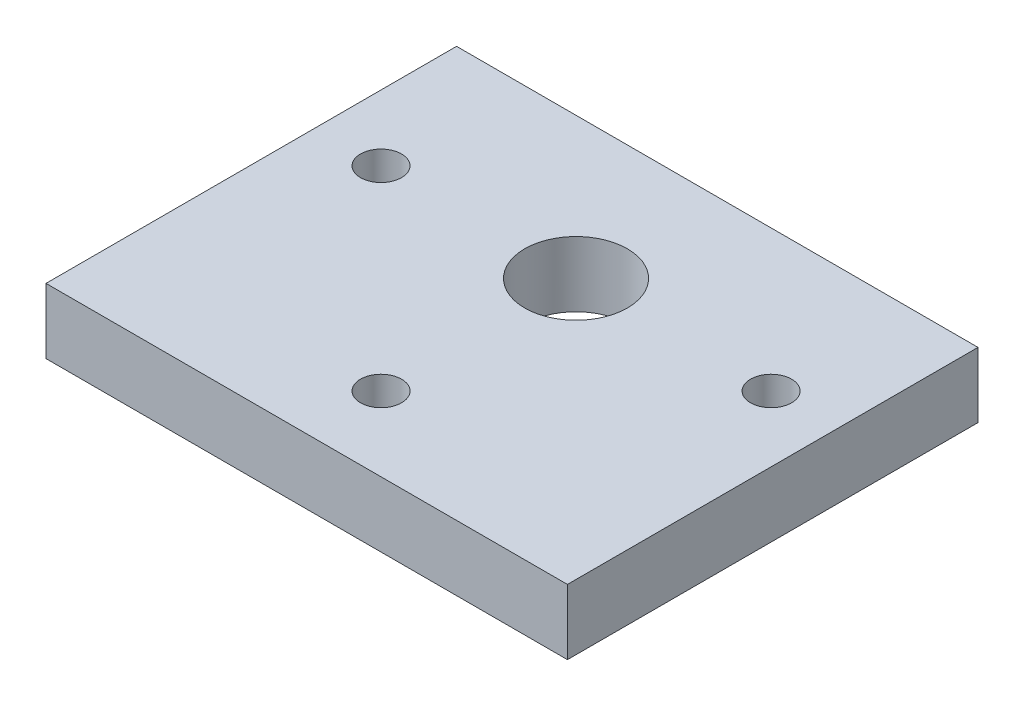
SolidWorks part; units mm, degrees
ref_plane "Alzado" through (0, 0, 0) normal (0, 0, 1) x (1, 0, 0)
ref_plane "Planta" through (0, 0, 0) normal (0, 1, 0) x (1, 0, 0)
ref_plane "Vista lateral" through (0, 0, 0) normal (1, 0, 0) x (0, 0, -1)
sketch "Croquis1" plane through (0, 0, 0) normal (0, 1, 0) x (1, 0, 0)
  line L1 (-25.4, 40) -> (25.4, 40)
  line L2 (-25.4, 40) -> (-25.4, -40)
  line L3 (-25.4, -40) -> (25.4, -40)
  line L4 (25.4, 40) -> (25.4, -40)
  line L5 (-25.4, 40) -> (25.4, -40) construction
  line L6 (-25.4, -40) -> (25.4, 40) construction
  point P0 (0, 0)
  dimension "D1" = 80
  dimension "D2" = 50.8
extrude "Saliente-Extruir1" add sketch "Croquis1" along normal blind 6.35
sketch "Croquis4" plane through (0, 6.35, 0) normal (0, 1, 0) x (1, 0, 0)
  circle A0 centre (-19, 19.4661) radius 2
  circle A1 centre (19, 19.4661) radius 2
  circle A2 centre (0, 0.4661) radius 2
  dimension "D3" = 4
  dimension "D5" = 4
  dimension "D4" = 4
  dimension "D1" = 38
  dimension "D2" = 19
  dimension "D6" = 19
extrude "Cortar-Extruir3" cut sketch "Croquis4" against normal through all
sketch "Croquis5" plane through (0, 6.35, 0) normal (0, 1, 0) x (1, 0, 0)
  line L0 (25.4, -40) -> (25.4, 40) construction
  line L1 (-25.4, -40) -> (25.4, -40)
  line L2 (-25.4, -40) -> (-25.4, -27.3)
  line L3 (-25.4, -27.3) -> (25.4, -27.3)
  line L4 (25.4, -40) -> (25.4, -27.3)
  dimension "D1" = 12.7
extrude "Cortar-Extruir4" cut sketch "Croquis5" against normal through all
sketch "Croquis6" plane through (0, 6.35, 0) normal (0, 1, 0) x (1, 0, 0)
  line L0 (25.4, -27.3) -> (25.4, 40) construction
  line L1 (-25.4, -27.3) -> (25.4, -27.3)
  line L2 (-25.4, -27.3) -> (-25.4, -6.7734)
  line L3 (-25.4, -6.7734) -> (25.4, -6.7734)
  line L4 (25.4, -27.3) -> (25.4, -6.7734)
extrude "Cortar-Extruir5" cut sketch "Croquis6" against normal blind 10
sketch "Croquis7" plane through (0, 0, 0) normal (0, -1, 0) x (1, 0, 0)
  line L0 (25.4, 6.7734) -> (25.4, -40) construction
  line L1 (-25.4, 6.7734) -> (25.4, 6.7734)
  line L2 (-25.4, 6.7734) -> (-25.4, -33.2266)
  line L3 (-25.4, -33.2266) -> (25.4, -33.2266)
  line L4 (25.4, 6.7734) -> (25.4, -33.2266)
  line L6 (-25.4, -33.2266) -> (25.4, -33.2266)
  line L7 (-25.4, -33.2266) -> (-25.4, -40)
  line L8 (-25.4, -40) -> (25.4, -40)
  line L9 (25.4, -33.2266) -> (25.4, -40)
  line M5 (25.4, -40) -> (25.4, 6.7734)
  line M7 (-25.4, 6.7734) -> (-25.4, -40)
  line M8 (-25.4, -40) -> (25.4, -40)
  dimension "D1" = 40
extrude "Cortar-Extruir6" cut sketch "Croquis7" against normal blind 10 contours L3 M7 M8 M5
sketch "Croquis9" plane through (0, 0, 0) normal (0, -1, 0) x (1, 0, 0)
  line L0 (-19, -19.4661) -> (19, -19.4661) construction
  circle A0 centre (0, -19.4661) radius 5
  dimension "D1" = 10
extrude "Cortar-Extruir7" cut sketch "Croquis9" against normal blind 10
equation "\"D2@Croquis4\"=\"D1@Croquis4\"/2"
equation "\"D5@Croquis4\"=\"D3@Croquis4\""
equation "\"D4@Croquis4\"=\"D3@Croquis4\""
